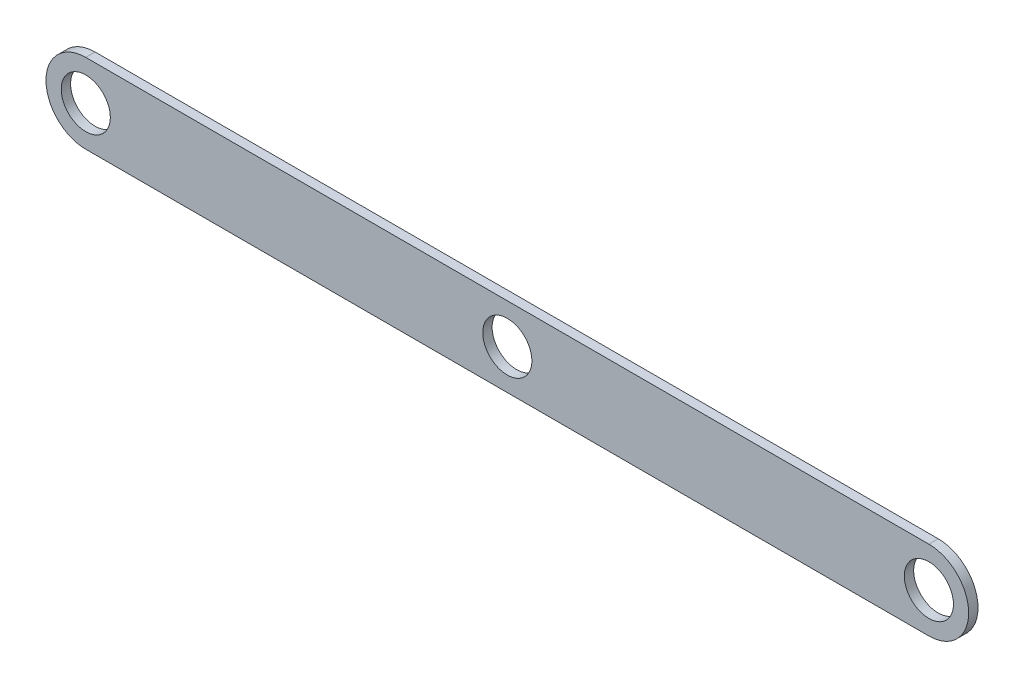
SolidWorks part; units mm, degrees
ref_plane "Vorne" through (0, 0, 0) normal (0, 0, 1) x (1, 0, 0)
ref_plane "Oben" through (0, 0, 0) normal (0, 1, 0) x (1, 0, 0)
ref_plane "Seite" through (0, 0, 0) normal (1, 0, 0) x (0, 0, -1)
sketch "Skizze2" plane through (0, 0, 0) normal (0, 0, 1) x (1, 0, 0)
  line L0 (50, 0) -> (-50, 0) construction
  line L1 (-90.1, 8.5) -> (90.1, 8.5)
  line L2 (-90.1, -8.5) -> (90.1, -8.5)
  line L3 (0, 8.5) -> (0, -8.5) construction
  arc A0 (-90.1, 8.5) -> (-90.1, -8.5) centre (-90.1, 0) ccw
  arc A1 (90.1, -8.5) -> (90.1, 8.5) centre (90.1, 0) ccw
  circle A2 centre (-90.1, 0) radius 5.25
  circle A3 centre (90.1, 0) radius 5.25
  circle A4 centre (0, 0) radius 5.25
  dimension "D1" = 10.5
  dimension "D2" = 180.2
  dimension "D3" = 17
extrude "Aufsatz-Linear austragen1" add sketch "Skizze2" along normal blind 2
